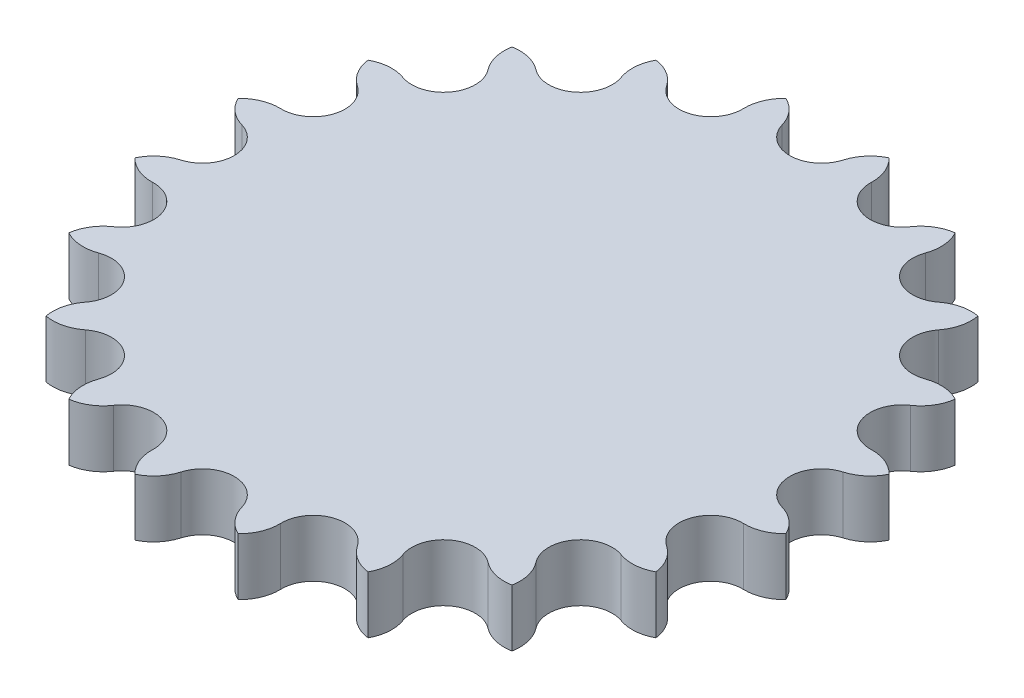
SolidWorks part; units mm, degrees
ref_plane "Alzado" through (0, 0, 0) normal (0, 0, 1) x (1, 0, 0)
ref_plane "Planta" through (0, 0, 0) normal (0, 1, 0) x (1, 0, 0)
ref_plane "Vista lateral" through (0, 0, 0) normal (1, 0, 0) x (0, 0, -1)
sketch "Croquis1" plane through (0, 0, 0) normal (0, 1, 0) x (1, 0, 0)
  line L0 (8.643, 36.4904) -> (9.8277, 41.492) construction
  line L1 (0, -46.904) -> (0, 46.904) construction
  circle A0 centre (0, 0) radius 37.5 construction
  circle A1 centre (0, 0) radius 42.64 construction
  circle A2 centre (0, 0) radius 39 construction
  arc A3 (-3.8413, 37.8846) -> (3.8413, 37.8846) centre (0, 39) ccw
  arc A5 (6.4946, 41.0053) -> (3.8413, 37.8846) centre (8.643, 36.4904) ccw
  arc A6 (-6.4946, 41.0053) -> (-3.8413, 37.8846) centre (-8.643, 36.4904) cw
  arc A7 (6.4946, 41.0053) -> (8.0537, 37.2175) centre (3.0561, 37.3753) cw
  arc A8 (8.0537, 37.2175) -> (15.3603, 34.8434) centre (12.0517, 37.0912) ccw
  arc A9 (18.8481, 36.9914) -> (15.3603, 34.8434) centre (19.4962, 32.0336) ccw
  arc A10 (18.8481, 36.9914) -> (19.1603, 32.9072) centre (14.4562, 34.6016) cw
  arc A11 (19.1603, 32.9072) -> (25.3757, 28.3914) centre (22.9236, 31.5517) ccw
  arc A12 (29.3565, 29.3565) -> (25.3757, 28.3914) centre (28.4409, 24.4411) ccw
  arc A13 (29.3565, 29.3565) -> (28.3914, 25.3757) centre (24.4411, 28.4409) cw
  arc A14 (28.3914, 25.3757) -> (32.9072, 19.1603) centre (31.5517, 22.9236) ccw
  arc A15 (36.9914, 18.8481) -> (32.9072, 19.1603) centre (34.6016, 14.4562) ccw
  arc A16 (36.9914, 18.8481) -> (34.8434, 15.3603) centre (32.0336, 19.4962) cw
  arc A17 (34.8434, 15.3603) -> (37.2175, 8.0537) centre (37.0912, 12.0517) ccw
  arc A18 (41.0053, 6.4946) -> (37.2175, 8.0537) centre (37.3753, 3.0561) ccw
  arc A19 (41.0053, 6.4946) -> (37.8846, 3.8413) centre (36.4904, 8.643) cw
  arc A20 (37.8846, 3.8413) -> (37.8846, -3.8413) centre (39, 0) ccw
  arc A21 (41.0053, -6.4946) -> (37.8846, -3.8413) centre (36.4904, -8.643) ccw
  arc A22 (41.0053, -6.4946) -> (37.2175, -8.0537) centre (37.3753, -3.0561) cw
  arc A23 (37.2175, -8.0537) -> (34.8434, -15.3603) centre (37.0912, -12.0517) ccw
  arc A24 (36.9914, -18.8481) -> (34.8434, -15.3603) centre (32.0336, -19.4962) ccw
  arc A25 (36.9914, -18.8481) -> (32.9072, -19.1603) centre (34.6016, -14.4562) cw
  arc A26 (32.9072, -19.1603) -> (28.3914, -25.3757) centre (31.5517, -22.9236) ccw
  arc A27 (29.3565, -29.3565) -> (28.3914, -25.3757) centre (24.4411, -28.4409) ccw
  arc A28 (29.3565, -29.3565) -> (25.3757, -28.3914) centre (28.4409, -24.4411) cw
  arc A29 (25.3757, -28.3914) -> (19.1603, -32.9072) centre (22.9236, -31.5517) ccw
  arc A30 (18.8481, -36.9914) -> (19.1603, -32.9072) centre (14.4562, -34.6016) ccw
  arc A31 (18.8481, -36.9914) -> (15.3603, -34.8434) centre (19.4962, -32.0336) cw
  arc A32 (15.3603, -34.8434) -> (8.0537, -37.2175) centre (12.0517, -37.0912) ccw
  arc A33 (6.4946, -41.0053) -> (8.0537, -37.2175) centre (3.0561, -37.3753) ccw
  arc A34 (6.4946, -41.0053) -> (3.8413, -37.8846) centre (8.643, -36.4904) cw
  arc A35 (3.8413, -37.8846) -> (-3.8413, -37.8846) centre (0, -39) ccw
  arc A36 (-6.4946, -41.0053) -> (-3.8413, -37.8846) centre (-8.643, -36.4904) ccw
  arc A37 (-6.4946, -41.0053) -> (-8.0537, -37.2175) centre (-3.0561, -37.3753) cw
  arc A38 (-8.0537, -37.2175) -> (-15.3603, -34.8434) centre (-12.0517, -37.0912) ccw
  arc A39 (-18.8481, -36.9914) -> (-15.3603, -34.8434) centre (-19.4962, -32.0336) ccw
  arc A40 (-18.8481, -36.9914) -> (-19.1603, -32.9072) centre (-14.4562, -34.6016) cw
  arc A41 (-19.1603, -32.9072) -> (-25.3757, -28.3914) centre (-22.9236, -31.5517) ccw
  arc A42 (-29.3565, -29.3565) -> (-25.3757, -28.3914) centre (-28.4409, -24.4411) ccw
  arc A43 (-29.3565, -29.3565) -> (-28.3914, -25.3757) centre (-24.4411, -28.4409) cw
  arc A44 (-28.3914, -25.3757) -> (-32.9072, -19.1603) centre (-31.5517, -22.9236) ccw
  arc A45 (-36.9914, -18.8481) -> (-32.9072, -19.1603) centre (-34.6016, -14.4562) ccw
  arc A46 (-36.9914, -18.8481) -> (-34.8434, -15.3603) centre (-32.0336, -19.4962) cw
  arc A47 (-34.8434, -15.3603) -> (-37.2175, -8.0537) centre (-37.0912, -12.0517) ccw
  arc A48 (-41.0053, -6.4946) -> (-37.2175, -8.0537) centre (-37.3753, -3.0561) ccw
  arc A49 (-41.0053, -6.4946) -> (-37.8846, -3.8413) centre (-36.4904, -8.643) cw
  arc A50 (-37.8846, -3.8413) -> (-37.8846, 3.8413) centre (-39, 0) ccw
  arc A51 (-41.0053, 6.4946) -> (-37.8846, 3.8413) centre (-36.4904, 8.643) ccw
  arc A52 (-41.0053, 6.4946) -> (-37.2175, 8.0537) centre (-37.3753, 3.0561) cw
  arc A53 (-37.2175, 8.0537) -> (-34.8434, 15.3603) centre (-37.0912, 12.0517) ccw
  arc A54 (-36.9914, 18.8481) -> (-34.8434, 15.3603) centre (-32.0336, 19.4962) ccw
  arc A55 (-36.9914, 18.8481) -> (-32.9072, 19.1603) centre (-34.6016, 14.4562) cw
  arc A56 (-32.9072, 19.1603) -> (-28.3914, 25.3757) centre (-31.5517, 22.9236) ccw
  arc A57 (-29.3565, 29.3565) -> (-28.3914, 25.3757) centre (-24.4411, 28.4409) ccw
  arc A58 (-29.3565, 29.3565) -> (-25.3757, 28.3914) centre (-28.4409, 24.4411) cw
  arc A59 (-25.3757, 28.3914) -> (-19.1603, 32.9072) centre (-22.9236, 31.5517) ccw
  arc A60 (-18.8481, 36.9914) -> (-19.1603, 32.9072) centre (-14.4562, 34.6016) ccw
  arc A61 (-18.8481, 36.9914) -> (-15.3603, 34.8434) centre (-19.4962, 32.0336) cw
  arc A62 (-15.3603, 34.8434) -> (-8.0537, 37.2175) centre (-12.0517, 37.0912) ccw
  arc A63 (-6.4946, 41.0053) -> (-8.0537, 37.2175) centre (-3.0561, 37.3753) ccw
  point P151 (0, 0)
  dimension "D1" = 78
  dimension "D2" = 85.28
  dimension "D3" = 75
  dimension "D4" = 8
  dimension "D5" = 20
extrude "Saliente-Extruir2" add sketch "Croquis1" along normal mid plane 7.2
